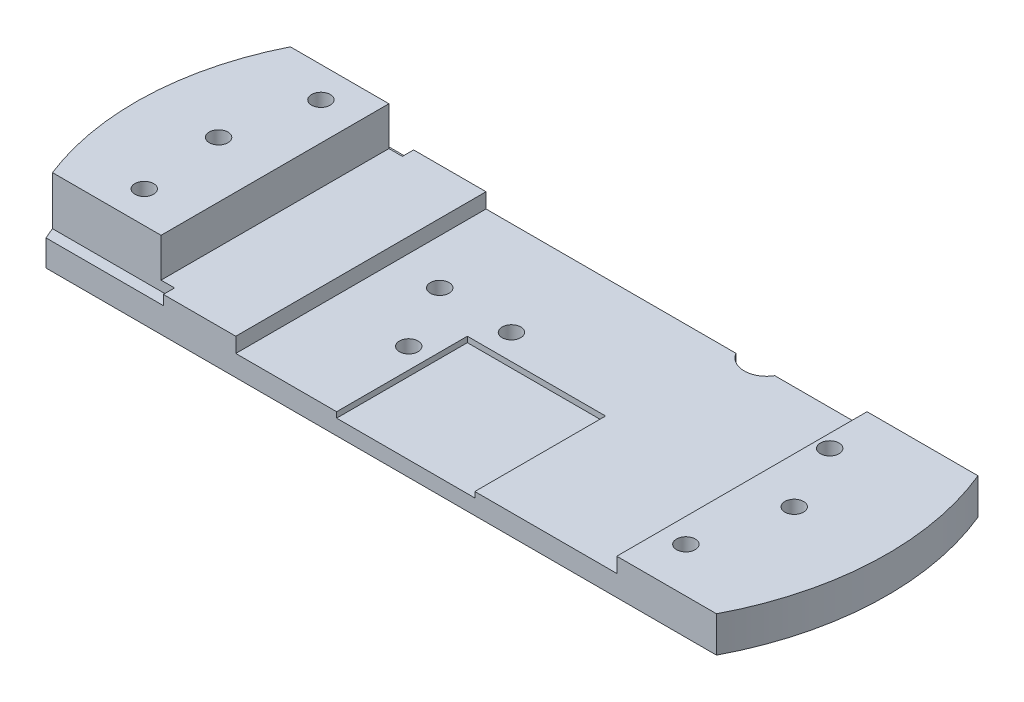
SolidWorks part; units mm, degrees
ref_plane "Front Plane" through (0, 0, 0) normal (0, 0, 1) x (1, 0, 0)
ref_plane "Top Plane" through (0, 0, 0) normal (0, 1, 0) x (1, 0, 0)
ref_plane "Right Plane" through (0, 0, 0) normal (1, 0, 0) x (0, 0, -1)
sketch "Sketch1" plane through (0, 0, 0) normal (0, 1, 0) x (1, 0, 0)
  line L1 (-97.5, -33.5) -> (97.5, -33.5)
  line L2 (-97.5, -33.5) -> (-97.5, 33.5)
  line L3 (-97.5, 33.5) -> (97.5, 33.5)
  line L4 (97.5, -33.5) -> (97.5, 33.5)
  line L5 (-97.5, -33.5) -> (97.5, 33.5) construction
  line L6 (-97.5, 33.5) -> (97.5, -33.5) construction
  point P0 (0, 0)
  dimension "D1" = 67
  dimension "D2" = 195
extrude "Boss-Extrude1" add sketch "Sketch1" along normal blind 20
sketch "Sketch2" plane through (0, 0, 0) normal (0, -1, 0) x (1, 0, 0)
  line L0 (-97.5, -33.5) -> (-97.5, 33.5) construction
  line L1 (97.5, 33.5) -> (97.5, -33.5) construction
  line L2 (97.5, 33.5) -> (88.5, 33.5)
  line L3 (-97.5, 33.5) -> (97.5, 33.5) construction
  line L4 (97.5, -33.5) -> (91.5, -33.5)
  line L5 (97.5, -33.5) -> (-97.5, -33.5) construction
  line L6 (-97.5, 33.5) -> (-91, 33.5)
  line L7 (-97.5, -33.5) -> (-88, -33.5)
  line L8 (-97.5, -33.5) -> (31.9, -33.5)
  line L9 (31.9, -30.5) -> (31.9, -36.5)
  line L10 (31.9, -33.5) -> (37.0962, -33.5)
  line L11 (97.5, -33.5) -> (-97.5, -33.5) construction
  circle A0 centre (18.0922, -3.2198) radius 79.4078
  circle A1 centre (-22.6589, 2.9929) radius 74.8411
  circle A5 centre (31.9, -36.5) radius 6
  line M7 (97.5, -33.5) -> (97.5, 33.5)
  line M8 (97.5, 33.5) -> (-97.5, 33.5)
  line M9 (-97.5, 33.5) -> (-97.5, -33.5)
  line M10 (-97.5, -33.5) -> (97.5, -33.5)
  dimension "D6" = 12
  dimension "D1" = 9
  dimension "D2" = 6
  dimension "D3" = 6.5
  dimension "D4" = 9.5
  dimension "D5" = 129.4
extrude "Cut-Extrude1" cut sketch "Sketch2" against normal blind 20 contours A0 M7 M8 | A0 M10 M7 | A1 M9 M10 | A1 M8 M9 | A5
sketch "Sketch3" plane through (0, 0, 33.5) normal (0, 0, -1) x (-1, 0, 0)
  line L0 (97.5, 20) -> (63.2, 20)
  line L1 (-91.5, 20) -> (-37.0962, 20) construction
  line L2 (63.2, 20) -> (63.2, 9.6)
  line L3 (63.2, 9.6) -> (40.2, 9.6)
  line L4 (40.2, 9.6) -> (40.2, 5.6)
  line L5 (40.2, 5.6) -> (-61.8, 5.6)
  line L7 (91, 20) -> (-88.5, 20) construction
  line L10 (97.5, 0) -> (97.5, 20) construction
  line L11 (-61.8, 5.6) -> (-61.8, 9.6)
  line L12 (-61.8, 9.6) -> (-97.5, 9.6)
  line L13 (-97.5, 20) -> (-97.5, 0) construction
  line L14 (-97.5, 9.6) -> (-97.5, 20)
  line L15 (-97.5, 20) -> (63.2, 20)
  line M13 (-88.5, 0) -> (-88.5, 20)
  line M14 (-88.5, 20) -> (91, 20)
  dimension "D1" = 10.4
  dimension "D2" = 34.3
  dimension "D3" = 23
  dimension "D4" = 4
  dimension "D5" = 102
extrude "Cut-Extrude2" cut sketch "Sketch3" along normal through all contours L11 L12 L2 L3 L4 L5 M13 M14
sketch "Sketch4" plane through (0, 20, 0) normal (0, 1, 0) x (1, 0, 0)
  line L0 (-59.5873, 33.5) -> (-59.5873, 30.5)
  line L1 (-63.2, 33.5) -> (-88, 33.5) construction
  line L2 (-59.5873, 30.5) -> (-89.5873, 30.5)
  line L3 (-59.5873, -33.5) -> (-59.5873, -30.5)
  line L4 (-91, -33.5) -> (-63.2, -33.5) construction
  line L5 (-59.5873, -30.5) -> (-92.2617, -30.5)
  line L6 (-59.5873, 33.5) -> (-63.2, 33.5)
  line L7 (-59.5873, -33.5) -> (-63.2, -33.5)
  arc A0 (-88, 33.5) -> (-91, -33.5) centre (-22.6589, -2.9929) ccw construction
  line M5 (-91, -33.5) -> (-63.2, -33.5)
  line M6 (-63.2, -33.5) -> (-63.2, 33.5)
  line M7 (-63.2, 33.5) -> (-88, 33.5)
  arc M8 (-88, 33.5) -> (-91, -33.5) centre (-22.6589, -2.9929) ccw
  dimension "D1" = 3
  dimension "D2" = 3
  dimension "D3" = 30
extrude "Cut-Extrude3" cut sketch "Sketch4" against normal blind 13 contours L2 M6 M7 M8 | L0 L6 L2 M6 | L5 M6 M8 M5 | L7 L3 L5 M6
sketch "Sketch6" plane through (0, 0, 0) normal (0, -1, 0) x (1, 0, 0)
  line L0 (-63.2, -33.5) -> (-97.5, -33.5)
  line L1 (26.7038, -33.5) -> (-88, -33.5) construction
  line L2 (-63.2, -33.5) -> (-63.2, 33.5)
  line L3 (-91, 33.5) -> (88.5, 33.5) construction
  line L4 (-63.2, -9) -> (-28.1, -9) construction
  line L5 (-63.2, 8.7) -> (-18.7, 8.7) construction
  line L6 (-63.2, -8.3) -> (-8.2, -8.3) construction
  line L8 (91.5, -33.5) -> (37.0962, -33.5) construction
  line L9 (-97.5, -33.5) -> (-97.5, 33.5)
  line L10 (-97.5, 33.5) -> (-63.2, 33.5)
  circle A0 centre (-28.1, -9) radius 2.5
  circle A1 centre (-18.7, 8.7) radius 2.5
  circle A2 centre (74.1, -1.7) radius 2.5
  circle A3 centre (68.3, 21.5) radius 2.5
  circle A4 centre (65.3, -20) radius 2.5
  circle A5 centre (-8.2, -8.3) radius 2.5
  circle A6 centre (-76.2, 22) radius 2.5
  circle A7 centre (-78.2, 0.1) radius 2.5
  circle A8 centre (-73.2, -22.3) radius 2.5
  arc A10 (-91, 33.5) -> (-88, -33.5) centre (-22.6589, 2.9929) ccw construction
  dimension "D2" = 5
  dimension "D3" = 35.1
  dimension "D4" = 34.3
  dimension "D5" = 44.5
  dimension "D6" = 24.5
  dimension "D7" = 55
  dimension "D8" = 42.2
  dimension "D9" = 137.3
  dimension "D10" = 128.5
  dimension "D11" = 131.5
  dimension "D12" = 10
  dimension "D13" = 15
  dimension "D14" = 13
  dimension "D15" = 11.2
  dimension "D16" = 33.6
  dimension "D17" = 55.5
  dimension "D18" = 31.8
  dimension "D19" = 55
  dimension "D20" = 13.5
  dimension "D21" = 25.2
extrude "Cut-Extrude4" cut sketch "Sketch6" against normal through all contours A0 | A5 | A1 | A6 | A7 | A8 | A4 | A2 | A3
sketch "Sketch7" plane through (0, 5.6, 0) normal (0, 1, 0) x (1, 0, 0)
  line L1 (-13.2, 1.5) -> (23.8, 1.5)
  line L2 (-13.2, 1.5) -> (-13.2, -33.5)
  line L3 (-13.2, -33.5) -> (23.8, -33.5)
  line L4 (23.8, 1.5) -> (23.8, -33.5)
  line L8 (-63.2, 30.5) -> (-63.2, -30.5) construction
  line L9 (-63.2, 30.5) -> (-63.2, -30.5) construction
  line L10 (-40.2, -33.5) -> (61.8, -33.5) construction
  dimension "D1" = 50
  dimension "D2" = 87
  dimension "D3" = 35
extrude "Cut-Extrude5" cut sketch "Sketch7" against normal blind 1.5
